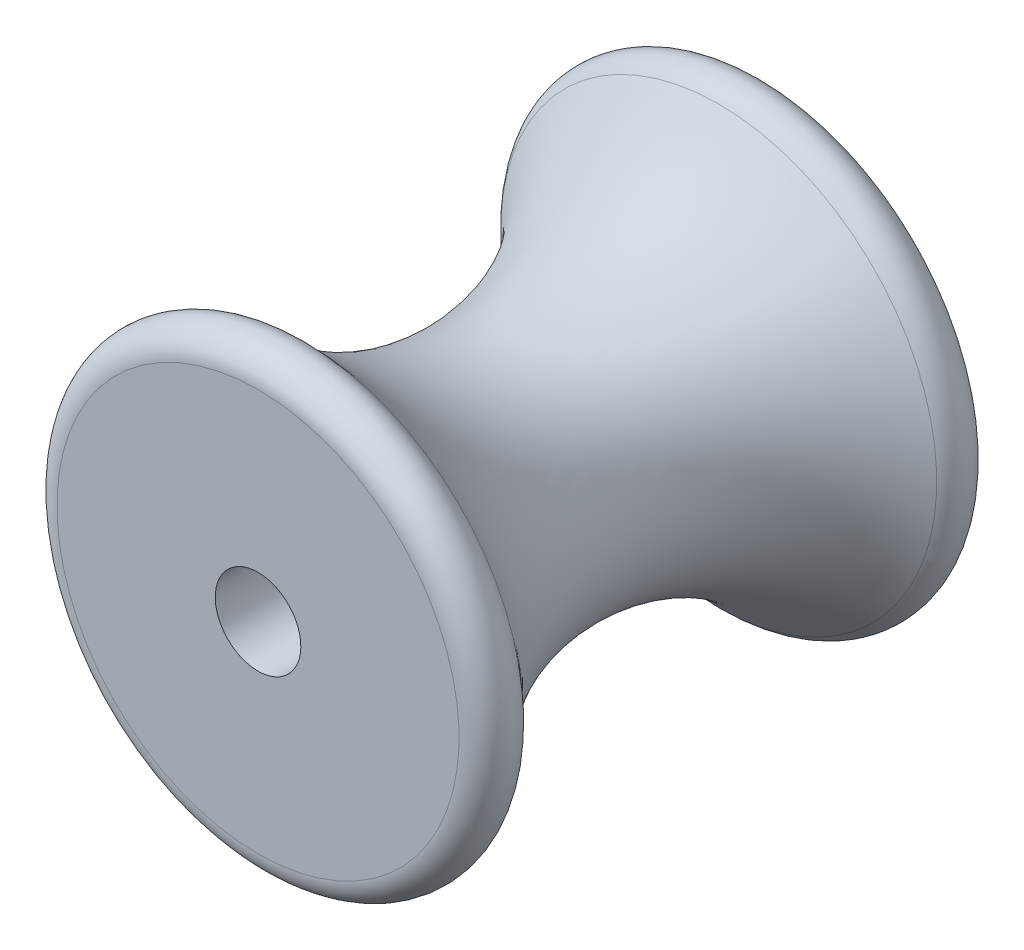
SolidWorks part; units mm, degrees
ref_plane "Front Plane" through (0, 0, 0) normal (0, 0, 1) x (1, 0, 0)
ref_plane "Top Plane" through (0, 0, 0) normal (0, 1, 0) x (1, 0, 0)
ref_plane "Right Plane" through (0, 0, 0) normal (1, 0, 0) x (0, 0, -1)
sketch "Sketch1" plane through (0, 0, 0) normal (1, 0, 0) x (0, 0, -1)
  line L0 (10, 0) -> (-10, 0) construction
  line L1 (10, 16.5) -> (10, -26.4787) construction
  line L2 (10, 1.6) -> (-10, 1.6) construction
  line L4 (0, 9.3697) -> (0, -9.3697) construction
  line L5 (10, 1.6) -> (10, 14.5) construction
  line L6 (-10, 1.6) -> (-10, 14.5) construction
  line L7 (9.5, 1.6) -> (9.5, 11.3775)
  line L8 (-9.5, 1.6) -> (-9.5, 11.3775)
  line L9 (9.5, 1.6) -> (-9.5, 1.6)
  circle A0 centre (0, 14.5) radius 10 construction
  arc A1 (9.5, 11.3775) -> (-9.5, 11.3775) centre (0, 14.5) cw
  point P2 (0, 0)
  dimension "D1" = 1
revolve "Revolve1" add sketch "Sketch1" angle 360 about L0
fillet "Fillet1" radius 1 2 edges at (0, 11.3775, 9.5) (0, 11.3775, -9.5)
